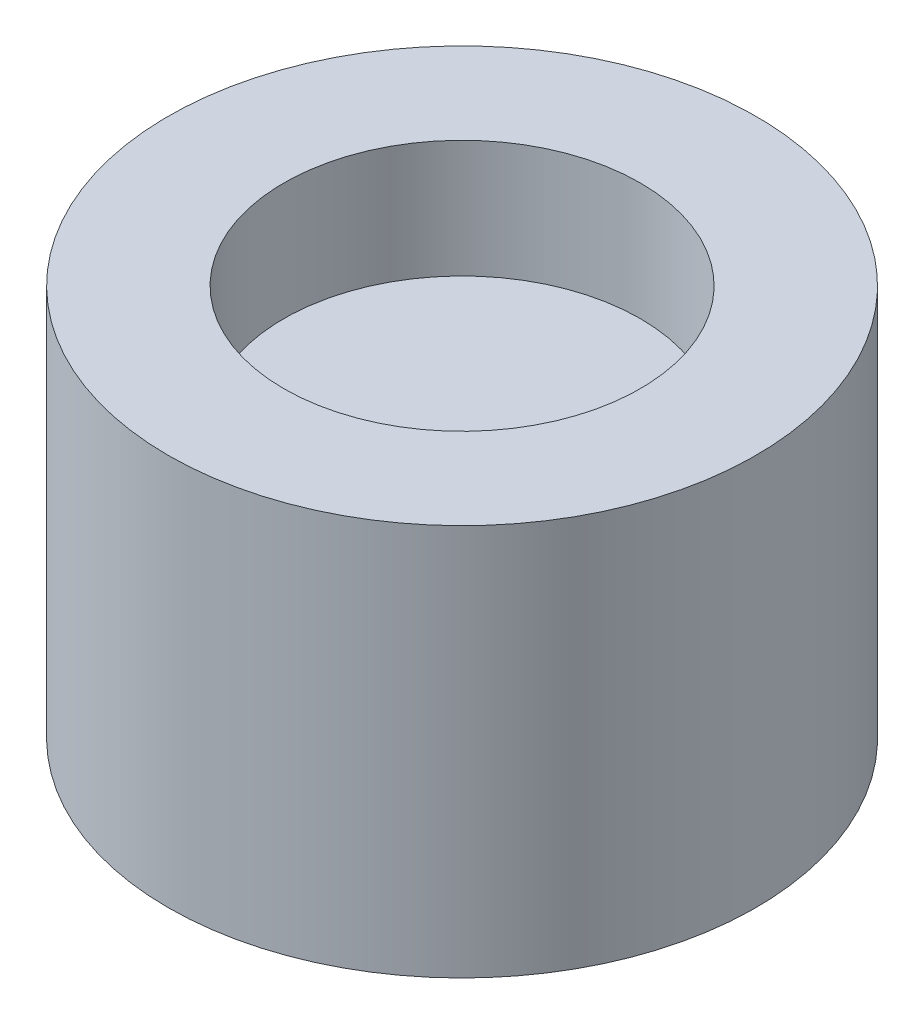
SolidWorks part; units mm, degrees
ref_plane "Front Plane" through (0, 0, 0) normal (0, 0, 1) x (1, 0, 0)
ref_plane "Top Plane" through (0, 0, 0) normal (0, 1, 0) x (1, 0, 0)
ref_plane "Right Plane" through (0, 0, 0) normal (1, 0, 0) x (0, 0, -1)
sketch "Sketch1" plane through (0, 0, 0) normal (0, 1, 0) x (1, 0, 0)
  circle A0 centre (0, 0) radius 7.5
  dimension "D1" = 15
extrude "Boss-Extrude2" add sketch "Sketch1" along normal blind 10
sketch "Sketch3" plane through (0, 10, 0) normal (0, 1, 0) x (1, 0, 0)
  circle A0 centre (0, 0) radius 4.55
  dimension "D1" = 9.1
extrude "Cut-Extrude1" cut sketch "Sketch3" against normal blind 3
